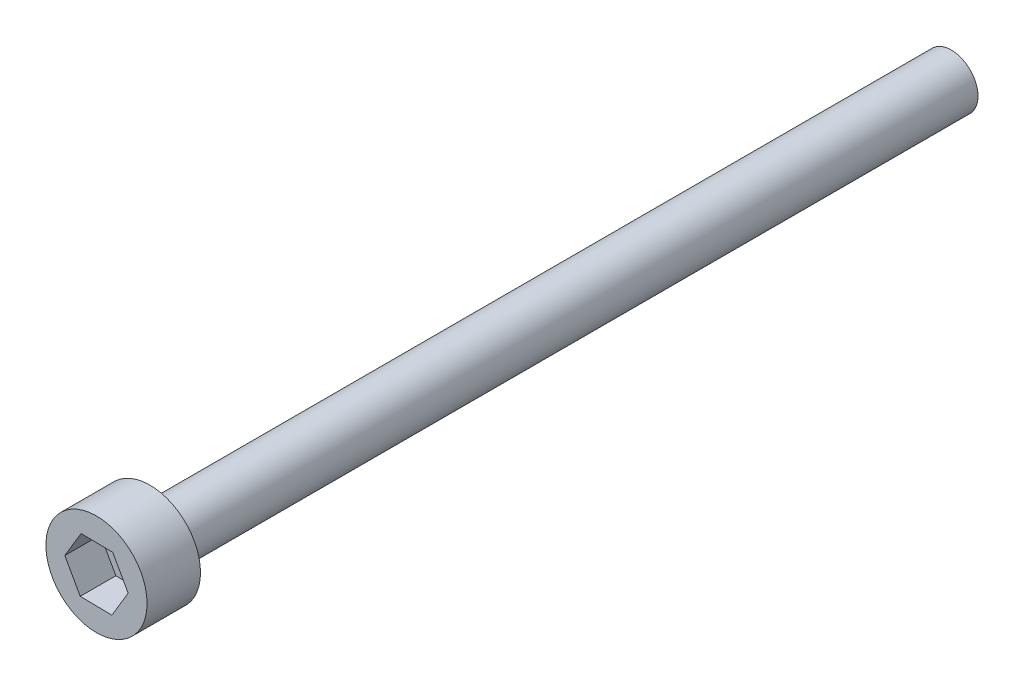
SolidWorks part; units mm, degrees
material "AISI 304"
ref_plane "前视基准面" through (0, 0, 0) normal (0, 0, 1) x (1, 0, 0)
ref_plane "上视基准面" through (0, 0, 0) normal (0, 1, 0) x (1, 0, 0)
ref_plane "右视基准面" through (0, 0, 0) normal (1, 0, 0) x (0, 0, -1)
sketch "草图1" plane through (0, 0, 0) normal (0, 0, 1) x (1, 0, 0)
  circle A0 centre (0, 0) radius 2.84
  dimension "D1" = 5.68
extrude "凸台-拉伸1" add sketch "草图1" along normal blind 3
sketch "草图2" plane through (0, 0, 0) normal (0, 0, -1) x (-1, 0, 0)
  circle A0 centre (0, 0) radius 1.5
  dimension "D1" = 3
extrude "凸台-拉伸2" add sketch "草图2" along normal blind 45
cosmetic thread "装饰螺纹线1" parameters "D2"=2
sketch "草图3" plane through (0, 0, 3) normal (0, 0, 1) x (1, 0, 0)
  line L1 (0.9126, 1.5262) -> (-0.8654, 1.5534)
  line L2 (-0.8654, 1.5534) -> (-1.778, 0.0272)
  line L3 (-1.778, 0.0272) -> (-0.9126, -1.5262)
  line L4 (-0.9126, -1.5262) -> (0.8654, -1.5534)
  line L5 (0.8654, -1.5534) -> (1.778, -0.0272)
  line L6 (1.778, -0.0272) -> (0.9126, 1.5262)
  circle A0 centre (0, 0) radius 1.54 construction
  dimension "D1" = 3.08
extrude "切除-拉伸1" cut sketch "草图3" against normal blind 2
